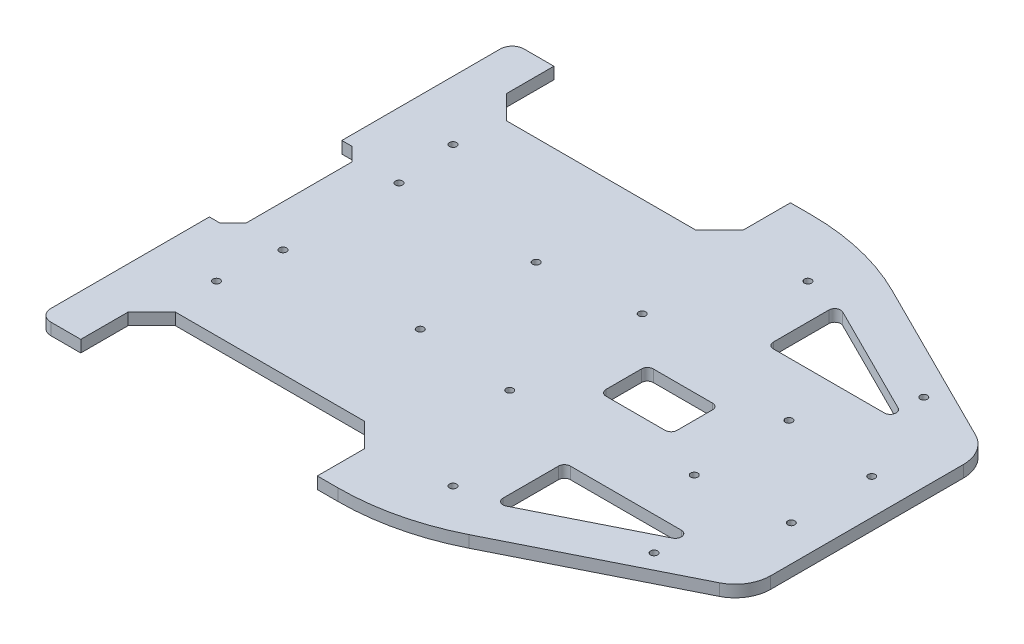
SolidWorks part; units mm, degrees
other "Markup1"
sketch "Sketch6" plane through (-125, 0, -100) normal (0, 1, 0) x (1, 0, 0)
other "Markup4"
sketch "Sketch12" plane through (-125, 0, -100) normal (0, 1, 0) x (1, 0, 0)
other "DetailItem1"
other "Markup5"
sketch "Sketch13" plane through (-125, 0, -100) normal (0, 1, 0) x (1, 0, 0)
other "DetailItem2"
other "DetailItem3"
other "DetailItem4"
other "Markup6"
sketch "Sketch14" plane through (-125, 0, -100) normal (0, 1, 0) x (1, 0, 0)
other "DetailItem5"
other "DetailItem6"
other "DetailItem7"
material "Acrylic (Medium-high impact)"
ref_plane "Front Plane" through (0, 0, 0) normal (0, 0, 1) x (1, 0, 0)
ref_plane "Top Plane" through (0, 0, 0) normal (0, 1, 0) x (1, 0, 0)
ref_plane "Right Plane" through (0, 0, 0) normal (1, 0, 0) x (0, 0, -1)
sketch "Sketch1" plane through (0, 0, 0) normal (0, 1, 0) x (1, 0, 0)
  line L0 (-55, 0) -> (55, 0) construction
  line L1 (-120, 100) -> (-107.362, 100)
  line L2 (-125, 95) -> (-125, -95)
  line L3 (-120, -100) -> (-107.362, -100)
  line L4 (125, 40.7295) -> (125, -40.7295)
  line L5 (-125, 100) -> (125, -100) construction
  line L6 (-125, -100) -> (125, 100) construction
  line L7 (46.1146, 89.4427) -> (116.7082, 54.1459)
  line L8 (46.1146, -89.4427) -> (116.7082, -54.1459)
  line L10 (-107.362, 100) -> (-107.362, 80)
  line L11 (-97.362, 70) -> (-17.362, 70)
  line L12 (-7.362, 100) -> (-7.362, 80)
  line L13 (-107.362, -100) -> (-107.362, -80)
  line L14 (-97.362, -70) -> (-17.362, -70)
  line L15 (-7.362, -100) -> (-7.362, -80)
  line L16 (-107.362, 80) -> (-97.362, 70)
  line L17 (-17.362, 70) -> (-7.362, 80)
  line L18 (-17.362, -70) -> (-7.362, -80)
  line L19 (-107.362, -80) -> (-97.362, -70)
  line L20 (-7.362, 100) -> (1.3932, 100)
  line L21 (-7.362, -100) -> (1.3932, -100)
  arc A0 (1.3932, -100) -> (46.1146, -89.4427) centre (1.3932, 0) ccw
  arc A1 (1.3932, 100) -> (46.1146, 89.4427) centre (1.3932, 0) cw
  arc A2 (116.7082, -54.1459) -> (125, -40.7295) centre (110, -40.7295) ccw
  arc A3 (116.7082, 54.1459) -> (125, 40.7295) centre (110, 40.7295) cw
  arc A4 (-125, -95) -> (-120, -100) centre (-120, -95) ccw
  arc A5 (-120, 100) -> (-125, 95) centre (-120, 95) ccw
  point P0 (0, 0)
  point P12 (25, -100)
  point P15 (25, 100)
  point P18 (125, -50)
  point P21 (125, 50)
  point P29 (-7.362, 70)
  point P30 (-107.362, 70)
  point P35 (-107.362, -70)
  point P36 (-7.362, -70)
  dimension "D7" = 100
  dimension "D8" = 15
  dimension "D9" = 5
  dimension "D1" = 200
  dimension "D2" = 250
  dimension "D3" = 100
  dimension "D4" = 100
  dimension "D5" = 50
  dimension "D6" = 100
  dimension "D10" = 30
  dimension "D11" = 100
extrude "Boss-Extrude2" add sketch "Sketch1" against normal blind 5
sketch "Sketch2" plane through (0, 0, 0) normal (0, 1, 0) x (1, 0, 0)
  line L0 (125, -40.7295) -> (125, 40.7295) construction
  circle A0 centre (110, 17) radius 1.5
  circle A1 centre (110, -17) radius 1.5
  dimension "D1" = 34
  dimension "D2" = 17
  dimension "D3" = 15
sketch "Sketch4" plane through (0, 0, 0) normal (0, 1, 0) x (1, 0, 0)
  line L0 (-39.3527, 24.5) -> (-39.3527, -24.5) construction
  circle A4 centre (-97.3527, -24.5) radius 1.5
  circle A5 centre (-39.3527, 24.5) radius 1.5
  circle A6 centre (-97.3527, 24.5) radius 1.5
  circle A7 centre (-39.3527, -24.5) radius 1.5
  point P8 (-39.3527, 0)
  dimension "D1" = 58
  dimension "D2" = 49
sketch "Sketch7" plane through (0, 0, 0) normal (0, 1, 0) x (1, 0, 0)
  line L0 (1.9669, 27.9982) -> (1.9669, -27.9982) construction
  line L6 (71.9669, 20.0059) -> (71.9669, -20.0059) construction
  line L7 (125, -40.7295) -> (125, 40.7295) construction
  line L9 (24.4669, 10.1951) -> (49.4669, 10.1951)
  line L10 (21.9669, 7.6951) -> (21.9669, -7.3049)
  line L11 (24.4669, -9.8049) -> (49.4669, -9.8049)
  line L12 (51.9669, 7.6951) -> (51.9669, -7.3049)
  line L13 (21.9669, 10.1951) -> (51.9669, -9.8049) construction
  line L14 (21.9669, -9.8049) -> (51.9669, 10.1951) construction
  arc A1 (49.4669, -9.8049) -> (51.9669, -7.3049) centre (49.4669, -7.3049) ccw
  circle A2 centre (1.9669, 27.9982) radius 1.5
  circle A7 centre (71.9669, 20.0059) radius 1.5
  circle A8 centre (1.9669, -28.0018) radius 1.5
  circle A9 centre (71.9669, -19.9941) radius 1.5
  arc A10 (21.9669, -7.3049) -> (24.4669, -9.8049) centre (24.4669, -7.3049) ccw
  arc A11 (24.4669, 10.1951) -> (21.9669, 7.6951) centre (24.4669, 7.6951) ccw
  arc A12 (49.4669, 10.1951) -> (51.9669, 7.6951) centre (49.4669, 7.6951) cw
  point P8 (1.9669, 0)
  point P11 (71.9669, 0)
  point P14 (125, 0)
  point P15 (36.9669, 0.1951)
  dimension "D3" = 70
  dimension "D4" = 30
  dimension "D1" = 56
  dimension "D7" = 2.5
  dimension "D2" = 40
  dimension "D5" = 20
  dimension "D6" = 35
extrude "Cut-Extrude6" cut sketch "Sketch7" against normal blind 5
extrude "Cut-Extrude7" cut sketch "Sketch2" against normal blind 5
extrude "Cut-Extrude8" cut sketch "Sketch4" against normal blind 5
sketch "Sketch10" plane through (0, 0, 0) normal (0, 1, 0) x (1, 0, 0)
  line L0 (-100, 50.0007) -> (-100, -50.0007) construction
  line L1 (-125, 95) -> (-125, -95) construction
  circle A0 centre (-100, 50.0007) radius 1.5
  circle A1 centre (-100, -49.9993) radius 1.5
  circle A2 centre (25, 75.0007) radius 1.5
  circle A3 centre (25, -74.9993) radius 1.5
  point P5 (-100, 0)
  dimension "D1" = 100
  dimension "D2" = 25
  dimension "D3" = 125
  dimension "D4" = 125
  dimension "D5" = 25
  dimension "D6" = 25
extrude "Cut-Extrude9" cut sketch "Sketch10" against normal blind 5
sketch "Sketch11" plane through (0, 0, 0) normal (0, 1, 0) x (1, 0, 0)
  line L0 (43.618, 71.0945) -> (90.5279, 47.6396)
  line L2 (40, 68.8585) -> (40, 45.4036)
  line L3 (42.5, 42.9036) -> (89.4098, 42.9036)
  line L5 (40, 72.9036) -> (100, 42.9036) construction
  line L6 (-125, 95) -> (-125, -95) construction
  line L7 (-2.75, 0) -> (2.75, 0) construction
  line L8 (40, -68.8585) -> (40, -45.4036)
  line L9 (42.5, -42.9036) -> (89.4098, -42.9036)
  line L10 (43.618, -71.0945) -> (90.5279, -47.6396)
  arc A0 (89.4098, -42.9036) -> (90.5279, -47.6396) centre (89.4098, -45.4036) cw
  arc A1 (40, -68.8585) -> (43.618, -71.0945) centre (42.5, -68.8585) ccw
  arc A2 (40, -45.4036) -> (42.5, -42.9036) centre (42.5, -45.4036) cw
  arc A3 (89.4098, 42.9036) -> (90.5279, 47.6396) centre (89.4098, 45.4036) ccw
  arc A4 (40, 45.4036) -> (42.5, 42.9036) centre (42.5, 45.4036) ccw
  arc A5 (43.618, 71.0945) -> (40, 68.8585) centre (42.5, 68.8585) ccw
  point P12 (100, -42.9036)
  point P15 (40, -72.9036)
  point P18 (40, -42.9036)
  point P24 (40, 42.9036)
  dimension "D4" = 2.5
  dimension "D1" = 60
  dimension "D2" = 30
  dimension "D3" = 165
extrude "Cut-Extrude10" cut sketch "Sketch11" against normal blind 5
sketch "Sketch15" plane through (0, 0, 0) normal (0, 1, 0) x (1, 0, 0)
  line L0 (116.7082, 54.1459) -> (46.1146, 89.4427) construction
  line L1 (125, -40.7295) -> (125, 40.7295) construction
  line L2 (125, 0) -> (92, 0) construction
  circle A0 centre (92, 56.9967) radius 1.5
  circle A1 centre (92, -56.9967) radius 1.5
  dimension "D1" = 3
  dimension "D2" = 8.5
  dimension "D3" = 33
extrude "Cut-Extrude11" cut sketch "Sketch15" against normal through all
sketch "Sketch16" plane through (0, 0, 0) normal (0, 1, 0) x (1, 0, 0)
  line L0 (-125, 95) -> (-125, -95) construction
  line L1 (-125, 28) -> (-120.6, 28)
  line L3 (-125, -28) -> (-120.6, -28)
  line L4 (-115, 22.4) -> (-115, -22.4)
  line L5 (-125, 0) -> (-115, -28) construction
  line L6 (-125, 0) -> (-115, 28) construction
  line L7 (-125, 28) -> (-125, -28)
  line L8 (-120.6, 28) -> (-115, 22.4)
  line L9 (-120.6, -28) -> (-115, -22.4)
  point P0 (-125, 0)
  dimension "D1" = 56
  dimension "D2" = 10
extrude "Cut-Extrude12" cut sketch "Sketch16" against normal blind 5
